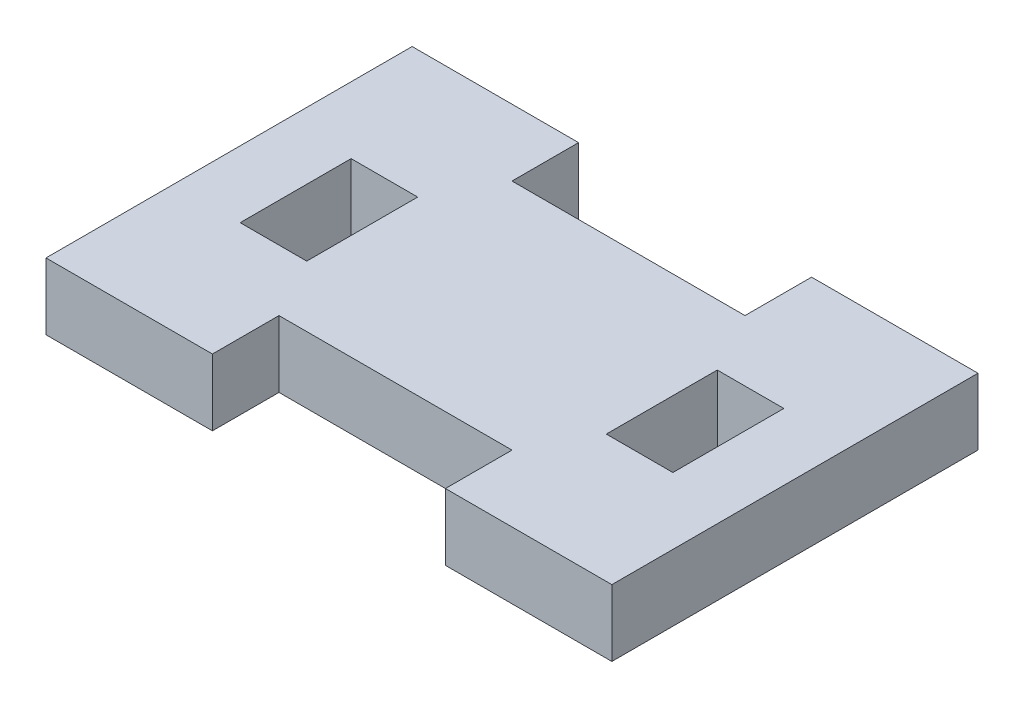
SolidWorks part; units mm, degrees
ref_plane "前视基准面" through (0, 0, 0) normal (0, 0, 1) x (1, 0, 0)
ref_plane "上视基准面" through (0, 0, 0) normal (0, 1, 0) x (1, 0, 0)
ref_plane "右视基准面" through (0, 0, 0) normal (1, 0, 0) x (0, 0, -1)
other "Configuration Table"
sketch "草图1" plane through (0, 0, 0) normal (0, 1, 0) x (1, 0, 0)
  line L0 (0, -8.25) -> (25.5, -8.25)
  line L21 (0, 0) -> (25.5, 0)
  line L22 (0, 0) -> (0, -16.5)
  line L23 (0, -16.5) -> (25.5, -16.5)
  line L24 (25.5, 0) -> (25.5, -16.5)
  line L25 (7.5, -16.5) -> (18, -16.5)
  line L26 (7.5, -16.5) -> (7.5, -13.5)
  line L27 (7.5, -13.5) -> (18, -13.5)
  line L28 (18, -16.5) -> (18, -13.5)
  line L29 (12.75, 0) -> (12.75, -16.5)
  line L30 (7.5, -3) -> (18, -3)
  line L31 (18, 0) -> (18, -3)
  line L32 (7.5, 0) -> (18, 0)
  line L33 (7.5, 0) -> (7.5, -3)
  line L34 (6, -10.75) -> (3, -10.75)
  line L35 (19.5, -5.75) -> (22.5, -5.75)
  line L36 (19.5, -5.75) -> (19.5, -10.75)
  line L37 (19.5, -10.75) -> (22.5, -10.75)
  line L38 (22.5, -5.75) -> (22.5, -10.75)
  line L39 (3, -5.75) -> (3, -10.75)
  line L40 (6, -5.75) -> (3, -5.75)
  line L41 (6, -5.75) -> (6, -10.75)
  dimension "D1" = 25.5
  dimension "D2" = 16.5
  dimension "D3" = 3
  dimension "D4" = 10.5
  dimension "D5" = 5.25
  dimension "D6" = 3
  dimension "D7" = 5
  dimension "D8" = 2.5
  dimension "D9" = 3
extrude "凸台-拉伸1" add sketch "草图1" along normal blind 3 contours L0 L41 L34 L39 L22 L23 L26 L27 L29 | L40 L41 L0 L29 L30 L33 L21 L22 L39 | L35 L38 L0 L24 L21 L31 L30 L29 L36 | L0 L38 L37 L36 L29 L27 L28 L23 L24
